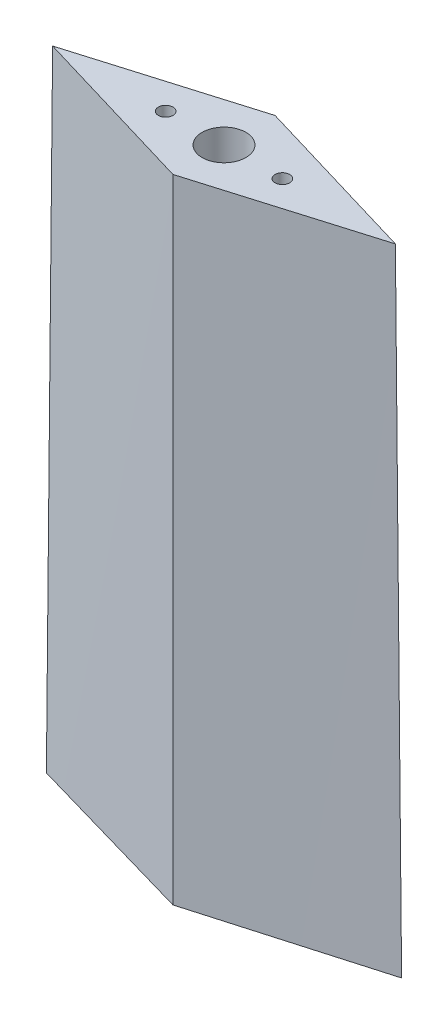
SolidWorks part; units mm, degrees
ref_plane "Front Plane" through (0, 0, 0) normal (0, 0, 1) x (1, 0, 0)
ref_plane "Top Plane" through (0, 0, 0) normal (0, 1, 0) x (1, 0, 0)
ref_plane "Right Plane" through (0, 0, 0) normal (1, 0, 0) x (0, 0, -1)
sketch "Sketch1" plane through (0, 0, 0) normal (0, 0, 1) x (1, 0, 0)
  line L0 (142.4212, 465.168) -> (219.716, 465.168)
  line L1 (219.716, 465.168) -> (213.5025, 1096.9676)
  line L2 (213.5025, 1096.9676) -> (181.0686, 1174.3372)
  line L3 (181.0686, 1174.3372) -> (148.6348, 1096.9676)
  line L4 (148.6348, 1096.9676) -> (142.4212, 465.168)
  point P2 (181.0686, 465.168)
extrude "Boss-Extrude1" add sketch "Sketch1" along normal blind 11.1125 and the other way blind 11.1125
sketch "Sketch2" plane through (0, 465.168, 0) normal (0, -1, 0) x (1, 0, 0)
  line L0 (142.4212, 0) -> (181.0686, 11.1125)
  line L1 (142.4212, -11.1125) -> (142.4212, 11.1125) construction
  line L2 (142.4212, 11.1125) -> (219.716, 11.1125) construction
  line L3 (181.0686, 11.1125) -> (219.716, 0)
  line L4 (219.716, -11.1125) -> (219.716, 11.1125) construction
  line L8 (142.4212, 0) -> (137.8486, 0)
  line L9 (137.8486, 0) -> (137.8486, 15.2584)
  line L10 (137.8486, 15.2584) -> (222.7051, 15.2584)
  line L11 (222.7051, 15.2584) -> (222.7051, 0)
  line L12 (222.7051, 0) -> (219.716, 0)
ref_plane "Plane1" through (0, 1096.9676, 0) normal (0, 1, 0) x (1, 0, 0)
sketch "Sketch3" plane through (0, 1096.9676, 0) normal (0, 1, 0) x (1, 0, 0)
  line L1 (148.6348, 11.1125) -> (148.6348, -11.1125) construction
  line L3 (213.5025, 11.1125) -> (213.5025, -11.1125) construction
  line L4 (213.5025, 0) -> (181.0686, -11.1125)
  line L5 (181.0686, -11.1125) -> (148.6348, 0)
  line L6 (148.6348, 0) -> (137.8486, 0)
  line L7 (137.8486, 0) -> (137.8486, -15.2584)
  line L8 (137.8486, -15.2584) -> (222.7051, -15.2584)
  line L9 (222.7051, -15.2584) -> (222.7051, 0)
  line L10 (222.7051, 0) -> (213.5025, 0)
loft "Cut-Loft1" cut profiles "Sketch2", "Sketch3"
mirror "Mirror1" about plane through (0, 0, 0) normal (0, 0, 1) of "Cut-Loft1"
ref_plane "Plane2" through (-32.1031, 13.4578, 93.6987) normal (-0.3212, 0.1346, 0.9374) x (0.947, 0.0457, 0.3179)
sketch "Sketch5" plane through (-32.1031, 13.4578, 93.6987) normal (-0.3212, 0.1346, 0.9374) x (0.947, 0.0457, 0.3179)
  line L1 (164.4105, 1280.8293) -> (274.288, 1280.8293)
  line L2 (164.4105, 1280.8293) -> (164.4105, 997.7782)
  line L3 (164.4105, 997.7782) -> (274.288, 997.7782)
  line L4 (274.288, 1280.8293) -> (274.288, 997.7782)
extrude "Cut-Extrude2" cut sketch "Sketch5" along normal through all
ref_plane "Plane3" through (69.4583, 29.1174, 202.7265) normal (0.3212, 0.1346, 0.9374) x (0.947, -0.0457, -0.3179)
sketch "Sketch6" plane through (69.4583, 29.1174, 202.7265) normal (0.3212, 0.1346, 0.9374) x (0.947, -0.0457, -0.3179)
  line L1 (57.1921, 1173.3831) -> (206.3136, 1173.3831)
  line L2 (57.1921, 1173.3831) -> (57.1921, 1064.4614)
  line L3 (57.1921, 1064.4614) -> (206.3136, 1064.4614)
  line L4 (206.3136, 1173.3831) -> (206.3136, 1064.4614)
extrude "Cut-Extrude3" cut sketch "Sketch6" along normal through all
mirror "Mirror2" about plane through (0, 0, 0) normal (0, 0, 1) of "Cut-Extrude2", "Cut-Extrude3"
sketch "Sketch7" plane through (0, 465.168, 0) normal (0, -1, 0) x (1, 0, 0)
  circle A0 centre (181.0686, 0) radius 4.7625
  dimension "D1" = 9.525
extrude "Cut-Extrude4" cut sketch "Sketch7" against normal blind 635
sketch "Sketch8" plane through (0, 0, 0) normal (0, 0, 1) x (1, 0, 0)
  line L0 (105.7103, 602.8372) -> (255.485, 602.8372)
  line L1 (105.7103, 1207.5881) -> (255.485, 1207.5881)
  line L2 (105.7103, 1207.5881) -> (105.7103, 454.0044)
  line L3 (105.7103, 454.0044) -> (255.485, 454.0044)
  line L4 (255.485, 1207.5881) -> (255.485, 454.0044)
  line L5 (255.485, 745.7122) -> (105.7103, 745.7122)
  line L6 (105.7103, 888.5872) -> (255.485, 888.5872)
  line L7 (255.485, 1031.4622) -> (105.7103, 1031.4622)
  dimension "D1" = 142.875
  dimension "D2" = 142.875
  dimension "D3" = 142.875
  dimension "D4" = 142.875
extrude "Cut-Extrude5" cut sketch "Sketch8" against normal through all and the other way through all contours L4 L5 L2 L0 | L6 L2 L5 L4 | L4 L7 L2 L6 | L7 L4 L1 L2
sketch "Sketch9" plane through (0, 465.168, 0) normal (0, -1, 0) x (1, 0, 0)
  circle A0 centre (168.3686, 0) radius 1.5875
  circle A1 centre (193.7686, 0) radius 1.5875
  circle A2 centre (181.0686, 0) radius 4.7625 construction
  dimension "D1" = 12.7
  dimension "D2" = 12.7
  dimension "D3" = 3.175
extrude "Cut-Extrude6" cut sketch "Sketch9" against normal blind 12.7
sketch "Sketch10" plane through (0, 602.8372, 0) normal (0, 1, 0) x (1, 0, 0)
  circle A0 centre (168.3686, 0) radius 1.5875
  circle A1 centre (193.7686, 0) radius 1.5875
  circle A2 centre (181.0686, 0) radius 4.7625 construction
  dimension "D2" = 12.7
  dimension "D3" = 3.175
  dimension "D4" = 0
  dimension "D1" = 12.7
extrude "Cut-Extrude7" cut sketch "Sketch10" against normal blind 12.7
